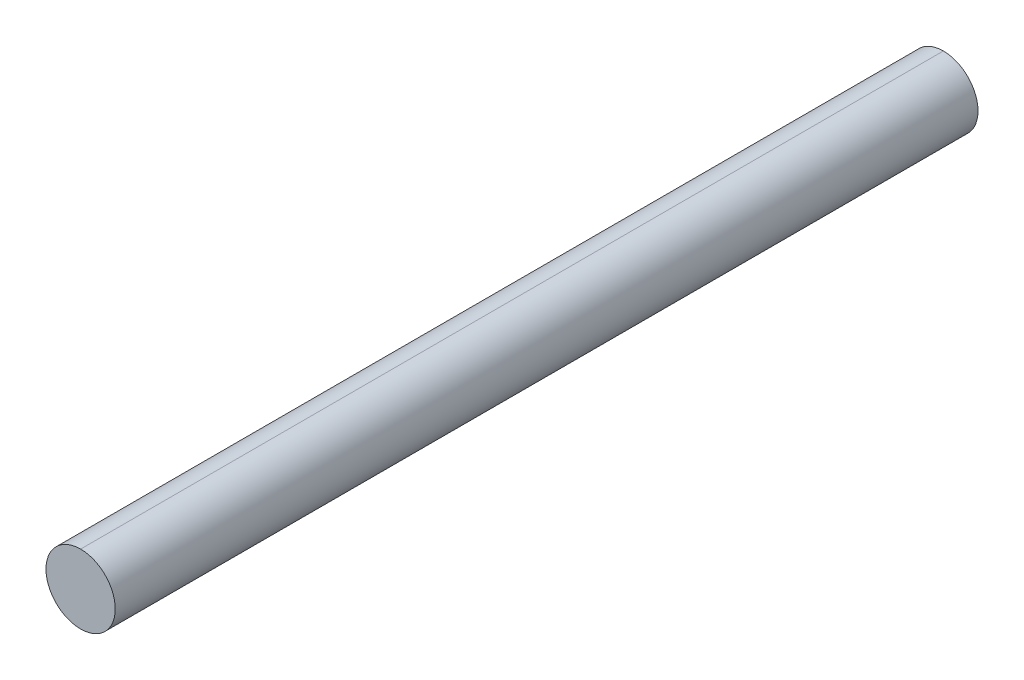
SolidWorks part; units mm, degrees
material "1060-O (SS)"
ref_plane "Front Plane" through (0, 0, 0) normal (0, 0, 1) x (1, 0, 0)
ref_plane "Top Plane" through (0, 0, 0) normal (0, 1, 0) x (1, 0, 0)
ref_plane "Right Plane" through (0, 0, 0) normal (1, 0, 0) x (0, 0, -1)
sketch "Sketch1" plane through (0, 0, 0) normal (0, 0, 1) x (1, 0, 0)
  circle A0 centre (0, 0) radius 12.2
extrude "Boss-Extrude1" add sketch "Sketch1" along normal blind 304
sketch "Sketch5" plane through (0, 0, 0) normal (0, 1, 0) x (1, 0, 0)
  line L0 (0, 0) -> (0, -304)
split line "Split Line1"
